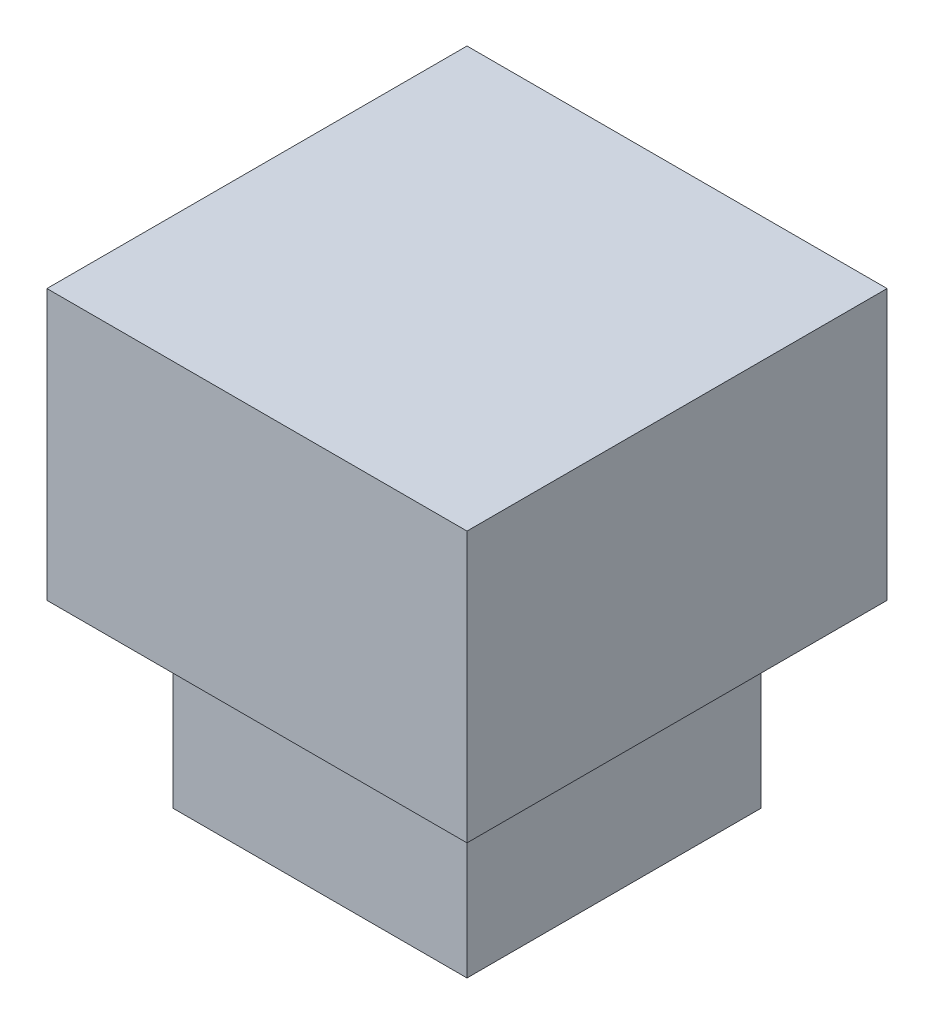
SolidWorks part; units mm, degrees
ref_plane "Alzado" through (0, 0, 0) normal (0, 0, 1) x (1, 0, 0)
ref_plane "Planta" through (0, 0, 0) normal (0, 1, 0) x (1, 0, 0)
ref_plane "Vista lateral" through (0, 0, 0) normal (1, 0, 0) x (0, 0, -1)
sketch "Croquis1" plane through (0, 0, 0) normal (0, 1, 0) x (1, 0, 0)
  line L1 (-2.45, -2.45) -> (2.45, -2.45)
  line L2 (-2.45, -2.45) -> (-2.45, 2.45)
  line L3 (-2.45, 2.45) -> (2.45, 2.45)
  line L4 (2.45, -2.45) -> (2.45, 2.45)
  line L5 (-2.45, -2.45) -> (2.45, 2.45) construction
  line L6 (-2.45, 2.45) -> (2.45, -2.45) construction
  point P0 (0, 0)
  dimension "D1" = 4.9
  dimension "D2" = 4.9
extrude "Saliente-Extruir1" add sketch "Croquis1" along normal blind 3
sketch "Croquis2" plane through (0, 3, 0) normal (0, 1, 0) x (1, 0, 0)
  line L1 (3.5, -3.5) -> (-3.5, -3.5)
  line L2 (3.5, -3.5) -> (3.5, 3.5)
  line L3 (3.5, 3.5) -> (-3.5, 3.5)
  line L4 (-3.5, -3.5) -> (-3.5, 3.5)
  line L5 (3.5, -3.5) -> (-3.5, 3.5) construction
  line L6 (3.5, 3.5) -> (-3.5, -3.5) construction
  point P0 (0, 0)
  dimension "D1" = 7
  dimension "D2" = 7
extrude "Saliente-Extruir2" add sketch "Croquis2" along normal blind 4.5
